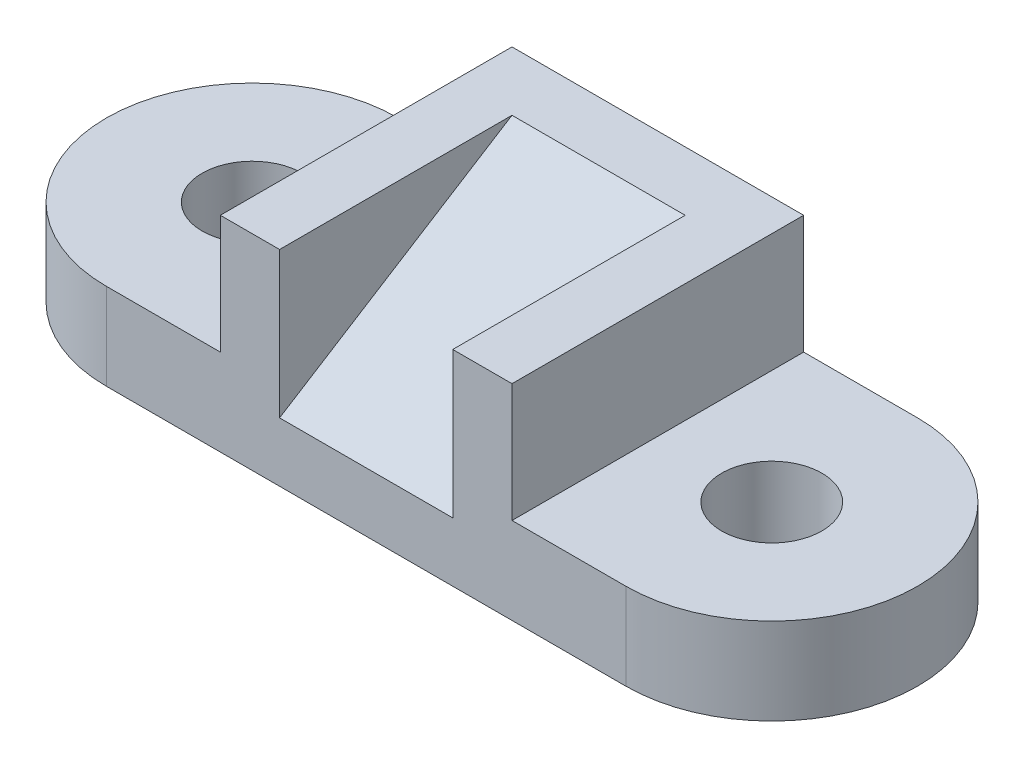
SolidWorks part; units mm, degrees
ref_plane "Front Plane" through (0, 0, 0) normal (0, 0, 1) x (1, 0, 0)
ref_plane "Top Plane" through (0, 0, 0) normal (0, 1, 0) x (1, 0, 0)
ref_plane "Right Plane" through (0, 0, 0) normal (1, 0, 0) x (0, 0, -1)
sketch "Sketch1" plane through (0, 0, 0) normal (0, 1, 0) x (1, 0, 0)
  line L1 (0, 0) -> (64, 0)
  line L2 (0, 0) -> (0, 64)
  line L3 (0, 64) -> (64, 64)
  line L4 (64, 0) -> (64, 64)
  dimension "D1" = 64
  dimension "D2" = 64
extrude "Boss-Extrude1" add sketch "Sketch1" along normal blind 45
sketch "Sketch2" plane through (0, 0, 0) normal (0, 1, 0) x (1, 0, 0)
  line L0 (0, 32) -> (-25, 32) construction
  line L1 (0, 64) -> (0, 0) construction
  line L2 (64, 32) -> (89, 32) construction
  line L3 (64, 0) -> (64, 64) construction
  line L4 (0, 64) -> (0, 0)
  line L5 (-25, 0) -> (0, 0)
  line L6 (-25, 64) -> (0, 64)
  line L7 (89, 52.513) -> (89, 9.9635) construction
  line L8 (89, 0) -> (64, 0)
  line L9 (89, 64) -> (64, 64)
  line L10 (64, 64) -> (64, 0)
  circle A0 centre (-25, 32) radius 11
  circle A1 centre (89, 32) radius 11
  arc A2 (-25, 64) -> (-25, 0) centre (-25, 32) ccw
  arc A3 (89, 0) -> (89, 64) centre (89, 32) ccw
  point P9 (0, 0)
  dimension "D2" = 22
  dimension "D3" = 22
  dimension "D4" = 25
  dimension "D5" = 64
  dimension "D6" = 64
  dimension "D1" = 114
  dimension "D7" = 25
  dimension "D8" = 25
extrude "Boss-Extrude4" add sketch "Sketch2" along normal blind 19
sketch "Sketch10" plane through (0, 0, 0) normal (0, 1, 0) x (1, 0, 0)
  line L0 (13, 0) -> (13, 51)
  line L1 (0, 0) -> (64, 0) construction
  line L2 (13, 51) -> (51, 51)
  line L3 (51, 51) -> (51, 0)
  line L4 (64, 64) -> (0, 64) construction
  line L5 (0, 0) -> (0, 64) construction
  line L6 (64, 64) -> (64, 0) construction
  line L7 (13, 0) -> (51, 0)
  dimension "D1" = 13
  dimension "D2" = 13
  dimension "D3" = 13
extrude "Cut-Extrude5" cut sketch "Sketch10" along normal blind 63
sketch "Sketch12" plane through (0, 0, 0) normal (0, 1, 0) x (1, 0, 0)
  line L1 (13, 51) -> (51, 51)
  line L2 (13, 51) -> (13, 0)
  line L3 (13, 0) -> (51, 0)
  line L4 (51, 51) -> (51, 0)
extrude "Boss-Extrude5" add sketch "Sketch12" along normal blind 13
sketch "Sketch13" plane through (13, 0, 0) normal (1, 0, 0) x (0, 0, -1)
  line L0 (0, 13) -> (51, 45)
  line L1 (51, 45) -> (51, 13)
  line L2 (51, 13) -> (0, 13)
extrude "Boss-Extrude6" add sketch "Sketch13" along normal blind 47
